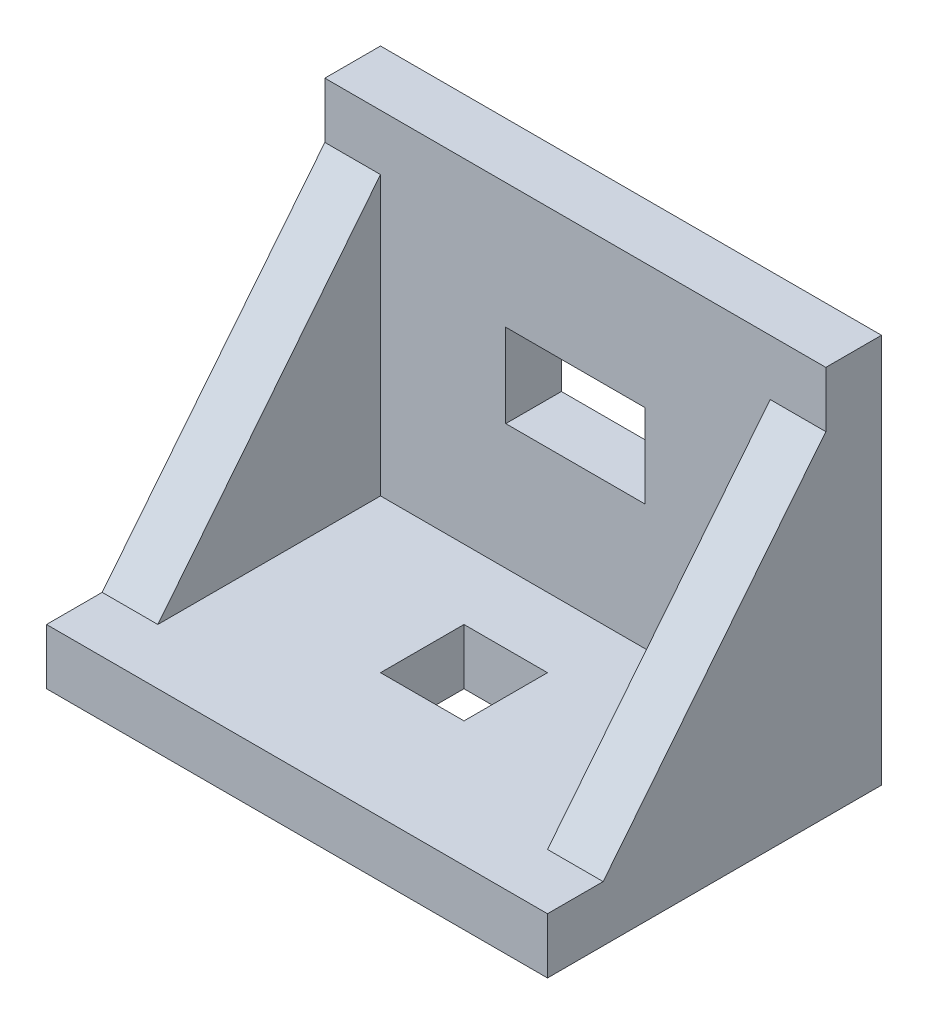
SolidWorks part; units mm, degrees
ref_plane "Front Plane" through (0, 0, 0) normal (0, 0, 1) x (1, 0, 0)
ref_plane "Top Plane" through (0, 0, 0) normal (0, 1, 0) x (1, 0, 0)
ref_plane "Right Plane" through (0, 0, 0) normal (1, 0, 0) x (0, 0, -1)
sketch "Sketch1" plane through (0, 0, 0) normal (0, 1, 0) x (1, 0, 0)
  line L1 (-45, 30) -> (45, 30)
  line L2 (-45, 30) -> (-45, -30)
  line L3 (-45, -30) -> (45, -30)
  line L4 (45, 30) -> (45, -30)
  line L5 (-45, 30) -> (45, -30) construction
  line L6 (-45, -30) -> (45, 30) construction
  point P0 (0, 0)
  dimension "D1" = 90
  dimension "D2" = 60
extrude "Boss-Extrude1" add sketch "Sketch1" along normal blind 10
sketch "Sketch2" plane through (0, 10, 0) normal (0, 1, 0) x (1, 0, 0)
  line L0 (45, -30) -> (45, 30) construction
  line L1 (-45, 30) -> (45, 30)
  line L2 (-45, 30) -> (-45, 20)
  line L3 (-45, 20) -> (45, 20)
  line L4 (45, 30) -> (45, 20)
  dimension "D1" = 10
extrude "Boss-Extrude2" add sketch "Sketch2" along normal blind 60
sketch "Sketch3" plane through (0, 0, -20) normal (0, 0, 1) x (1, 0, 0)
  line L5 (-12.5, 47.5) -> (12.5, 47.5)
  line L6 (-12.5, 47.5) -> (-12.5, 32.5)
  line L7 (-12.5, 32.5) -> (12.5, 32.5)
  line L8 (12.5, 47.5) -> (12.5, 32.5)
  line L9 (-12.5, 47.5) -> (12.5, 32.5) construction
  line L10 (-12.5, 32.5) -> (12.5, 47.5) construction
  point P0 (0, 40)
extrude "Cut-Extrude1" cut sketch "Sketch3" against normal blind 10
sketch "Sketch5" plane through (0, 10, 0) normal (0, 1, 0) x (1, 0, 0)
  line L1 (-7.5, 7.5) -> (7.5, 7.5)
  line L2 (-7.5, 7.5) -> (-7.5, -7.5)
  line L3 (-7.5, -7.5) -> (7.5, -7.5)
  line L4 (7.5, 7.5) -> (7.5, -7.5)
  line L5 (-7.5, 7.5) -> (7.5, -7.5) construction
  line L6 (-7.5, -7.5) -> (7.5, 7.5) construction
  point P0 (0, 0)
extrude "Cut-Extrude2" cut sketch "Sketch5" against normal blind 10
sketch "Sketch6" plane through (-45, 0, 0) normal (-1, 0, 0) x (0, 0, 1)
  line L0 (20, 10) -> (-20, 60)
  line L1 (-20, 10) -> (30, 10) construction
  line L2 (-20, 70) -> (-20, 10) construction
  point P9 (0, 0)
rib "Rib1" sketch "Sketch6" sketch "Sketch6" thickness 10 extrusion direction parallel to sketch draft on no parameters "D1"=10
mirror "Mirror1" about plane through (0, 0, 0) normal (1, 0, 0) of "Rib1"
